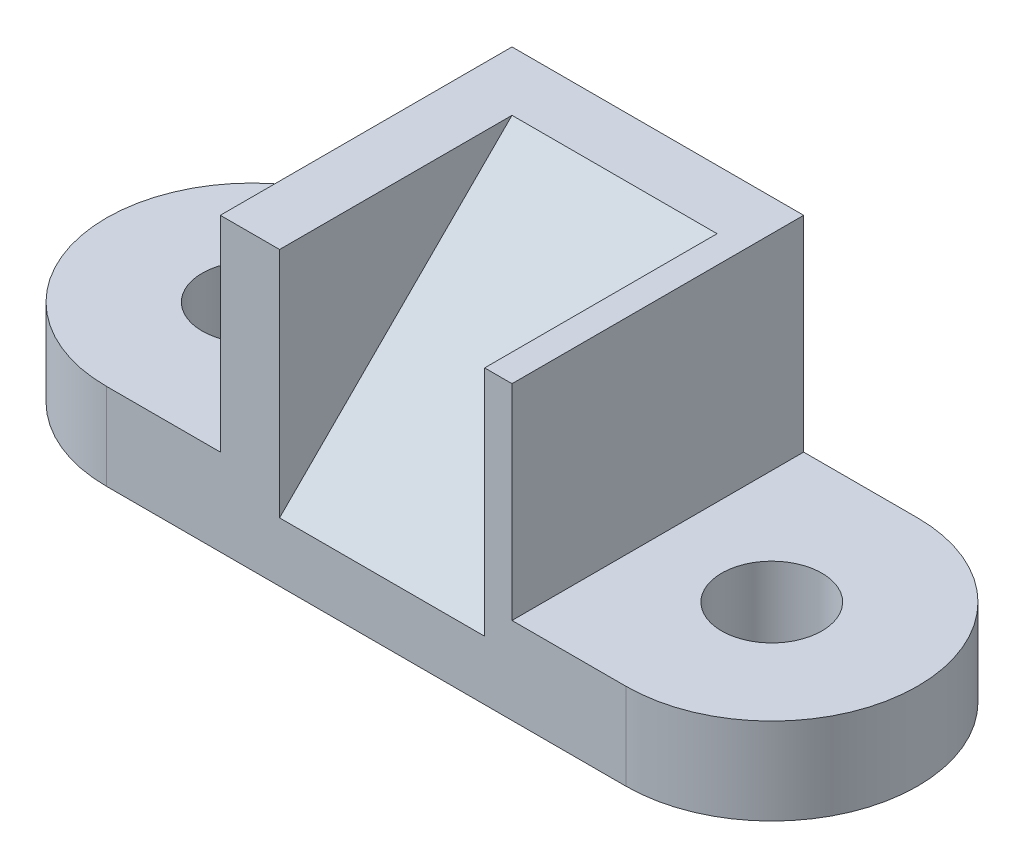
SolidWorks part; units mm, degrees
ref_plane "Front Plane" through (0, 0, 0) normal (0, 0, 1) x (1, 0, 0)
ref_plane "Top Plane" through (0, 0, 0) normal (0, 1, 0) x (1, 0, 0)
ref_plane "Right Plane" through (0, 0, 0) normal (1, 0, 0) x (0, 0, -1)
sketch "Sketch1" plane through (0, 0, 0) normal (0, 1, 0) x (1, 0, 0)
  line L0 (0, 0) -> (114, 0) construction
  line L1 (0, 32) -> (114, 32)
  line L2 (0, -32) -> (114, -32)
  arc A0 (0, 32) -> (0, -32) centre (0, 0) ccw
  arc A1 (114, -32) -> (114, 32) centre (114, 0) ccw
  circle A2 centre (0, 0) radius 11
  circle A3 centre (114, 0) radius 11
  point P3 (57, 0)
  dimension "D2" = 32
  dimension "D3" = 22
  dimension "D4" = 22
  dimension "D1" = 114
extrude "Boss-Extrude1" add sketch "Sketch1" along normal blind 19
sketch "Sketch2" plane through (0, 19, 0) normal (0, 1, 0) x (1, 0, 0)
  line L0 (57, 32) -> (57, -32) construction
  line L1 (114, 32) -> (0, 32) construction
  line L2 (0, -32) -> (114, -32) construction
  line L3 (25, 32) -> (25, -32)
  line L4 (25, 32) -> (89, 32)
  line L5 (57, 32) -> (57, -32) construction
  line L6 (25, -32) -> (89, -32)
  line L7 (89, 32) -> (89, -32)
  dimension "D1" = 32
  dimension "D2" = 64
extrude "Boss-Extrude2" add sketch "Sketch2" along normal blind 45 contours L6 L7 L4 L3
sketch "Sketch3" plane through (25, 0, 0) normal (-1, 0, 0) x (0, 0, 1)
  line L0 (32, 64) -> (-19, 64)
  line L1 (-32, 64) -> (32, 64) construction
  line L4 (-19, 64) -> (32, 13)
  line L5 (32, 19) -> (32, 0) construction
  line L6 (32, 13) -> (32, 64)
  dimension "D1" = 13
  dimension "D2" = 13
extrude "Cut-Extrude2" cut sketch "Sketch3" against normal blind 45 from offset 13 contours L6 L0 L4
